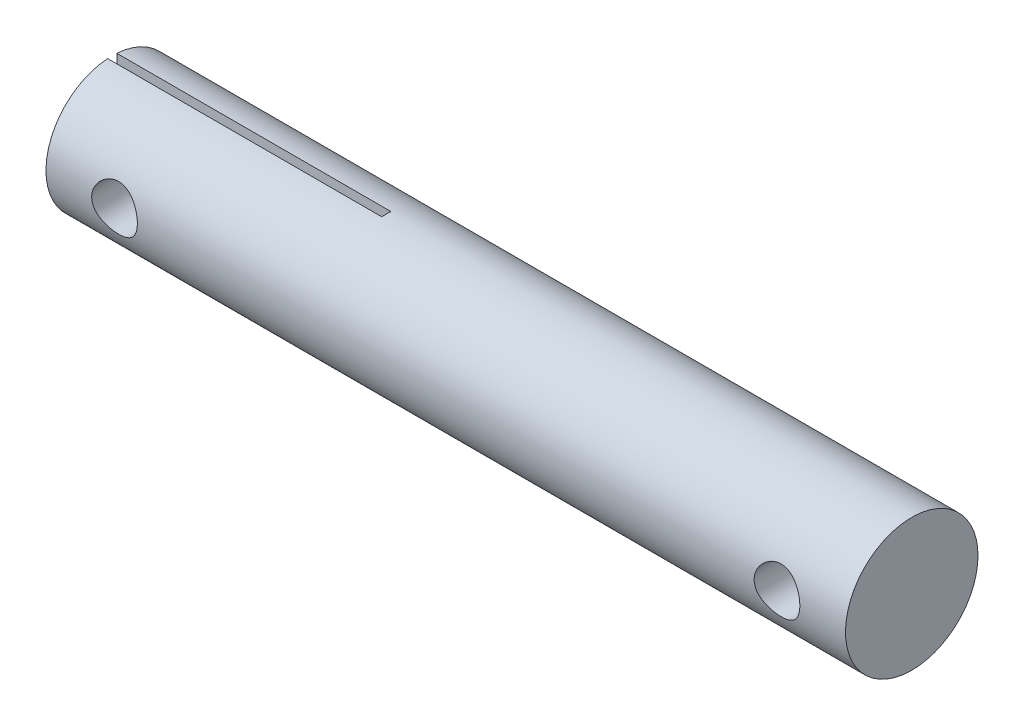
SolidWorks part; units mm, degrees
ref_plane "前视基准面" through (0, 0, 0) normal (0, 0, 1) x (1, 0, 0)
ref_plane "上视基准面" through (0, 0, 0) normal (0, 1, 0) x (1, 0, 0)
ref_plane "右视基准面" through (0, 0, 0) normal (1, 0, 0) x (0, 0, -1)
other "Configuration Table"
sketch "草图1" plane through (0, 0, 0) normal (1, 0, 0) x (0, 0, -1)
  circle A0 centre (0, 0) radius 2.9
  dimension "D1" = 5.8
extrude "凸台-拉伸1" add sketch "草图1" along normal blind 35
sketch "草图2" plane through (0, 0, 0) normal (-1, 0, 0) x (0, 0, 1)
  line L0 (0, 2.9) -> (0, -2.9) construction
  line L2 (-0.2, 3.1215) -> (0.2, 3.1215)
  line L3 (-0.2, 3.1215) -> (-0.2, -2.329)
  line L4 (-0.2, -2.329) -> (0.2, -2.329)
  line L5 (0.2, 3.1215) -> (0.2, -2.329)
  circle A0 centre (0, 0) radius 2.9 construction
  dimension "D1" = 0.4
  dimension "D2" = 0.2
extrude "切除-拉伸1" cut sketch "草图2" against normal blind 12
sketch "草图3" plane through (0, 0, 0.2) normal (0, 0, -1) x (-1, 0, 0)
  line L0 (0, -0.0035) -> (-6.0327, -0.0035) construction
  line L1 (0, -2.9) -> (0, 2.8931) construction
  line L2 (-35, 2.9) -> (-35, -2.9) construction
  circle A0 centre (-3, -0.0035) radius 1
  circle A1 centre (-32, -0.0035) radius 1
  dimension "D1" = 2
  dimension "D4" = 2
  dimension "D2" = 3
  dimension "D3" = 3
extrude "切除-拉伸2" cut sketch "草图3" against normal blind 10 and the other way blind 10
